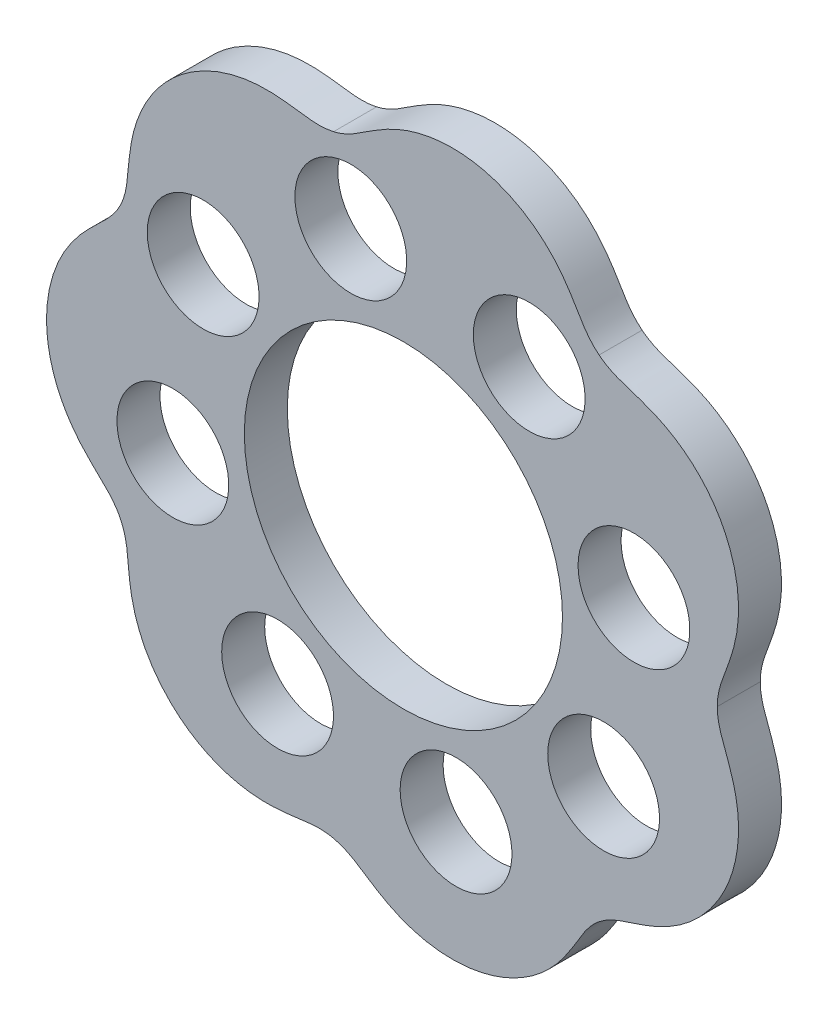
SolidWorks part; units mm, degrees
material "5052-H34"
ref_plane "Front Plane" through (0, 0, 0) normal (0, 0, 1) x (1, 0, 0)
ref_plane "Top Plane" through (0, 0, 0) normal (0, 1, 0) x (1, 0, 0)
ref_plane "Right Plane" through (0, 0, 0) normal (1, 0, 0) x (0, 0, -1)
sketch "Sketch1" plane through (0, 0, 0) normal (0, 0, 1) x (1, 0, 0)
  line L0 (0, 0) -> (37, 0) construction
  line L2 (37, 0) -> (39.5, 0) construction
  line L5 (24.6278, 30.8823) -> (0, 0) construction
  line L6 (0, 0) -> (-8.7896, 38.5096) construction
  line L7 (-35.5883, 17.1384) -> (0, 0) construction
  line L9 (-35.5883, -17.1384) -> (0, 0) construction
  line L10 (-8.7896, -38.5097) -> (0, 0) construction
  line L11 (24.6278, -30.8823) -> (0, 0) construction
  circle A0 centre (0, 0) radius 36 construction
  circle A1 centre (37, 0) radius 6 construction
  spline S0 degree 4 poles (39.9483, -2.12) (39.9195, -2.0383) (39.8632, -1.8746) (39.7822, -1.6278) (39.6848, -1.2955) (39.6113, -0.995) (39.5602, -0.7266) (39.5276, -0.4967) (39.5088, -0.2963) (39.4998, -0.0928) (39.4991, 0.0501) (39.505, 0.2155) (39.5157, 0.3724) (39.5329, 0.5353) (39.558, 0.7077) (39.6011, 0.9443) (39.6734, 1.255) (39.779, 1.6227) (39.9203, 2.0472) (40.0768, 2.4805) (40.3026, 3.083) (40.5945, 3.8559) (41.0315, 5.0877) (41.5249, 6.8077) (41.9013, 8.8642) (42.0339, 11.2502) (41.8633, 13.6337) (41.3936, 15.9767) (40.6339, 18.2422) (39.5972, 20.395) (38.2996, 22.4015) (36.7607, 24.2296) (35.0035, 25.849) (33.2989, 27.0601) (31.7392, 27.9386) (30.3866, 28.5643) (29.2788, 29.0047) (28.3249, 29.3341) (27.5386, 29.5876) (26.9268, 29.7867) (26.4905, 29.9345) (26.0706, 30.0887) (25.717, 30.2355) (25.4294, 30.3725) (25.184, 30.5045) (25.0052, 30.6109) (24.8304, 30.7289) (24.6664, 30.8504) (24.5552, 30.94) (24.4016, 31.074) (24.2567, 31.2136) (24.0973, 31.3824) (23.9194, 31.5897) (23.7303, 31.8345) (23.5312, 32.1179) (23.3886, 32.3351) (23.2958, 32.4812) (23.2499, 32.5546) knots 0 0 0 0 0 0.00783 0.015661 0.023491 0.031321 0.035802 0.040282 0.044763 0.049243 0.052611 0.055979 0.059347 0.062715 0.06731 0.071905 0.081096 0.091513 0.101931 0.112349 0.122766 0.149711 0.176657 0.230547 0.284438 0.338328 0.392219 0.446109 0.5 0.553891 0.607781 0.661672 0.715562 0.769453 0.796398 0.823343 0.850289 0.877234 0.887651 0.898069 0.908487 0.918904 0.928095 0.93269 0.937285 0.944021 0.947389 0.950757 0.955237 0.959718 0.964198 0.968679 0.976509 0.984339 0.99217 1 1 1 1 1 construction
  spline S1 degree 4 poles (39.5, 0) (39.5, 0.0336) (39.5009, 0.1009) (39.505, 0.2155) (39.5157, 0.3724) (39.5329, 0.5353) (39.558, 0.7077) (39.6011, 0.9443) (39.6734, 1.255) (39.779, 1.6227) (39.9203, 2.0472) (40.0768, 2.4805) (40.3026, 3.083) (40.5945, 3.8559) (41.0315, 5.0877) (41.5249, 6.8077) (41.9013, 8.8642) (42.0339, 11.2502) (41.8633, 13.6337) (41.3936, 15.9767) (40.6339, 18.2422) (39.5972, 20.395) (38.2996, 22.4015) (36.7607, 24.2296) (35.0035, 25.849) (33.2989, 27.0601) (31.7392, 27.9386) (30.3866, 28.5643) (29.2788, 29.0047) (28.3249, 29.3341) (27.5386, 29.5876) (26.9268, 29.7867) (26.4905, 29.9345) (26.0706, 30.0887) (25.717, 30.2355) (25.4294, 30.3725) (25.184, 30.5045) (25.0052, 30.6109) (24.8304, 30.7289) (24.7073, 30.8201) (24.6541, 30.8614) (24.6278, 30.8823) knots 0.049243 0.049243 0.049243 0.049243 0.049243 0.052611 0.055979 0.059347 0.062715 0.06731 0.071905 0.081096 0.091513 0.101931 0.112349 0.122766 0.149711 0.176657 0.230547 0.284438 0.338328 0.392219 0.446109 0.5 0.553891 0.607781 0.661672 0.715562 0.769453 0.796398 0.823343 0.850289 0.877234 0.887651 0.898069 0.908487 0.918904 0.928095 0.93269 0.937285 0.944021 0.947389 0.950757 0.950757 0.950757 0.950757 0.950757 construction
  spline S2 degree 4 poles (23.2499, -32.5546) (23.2958, -32.4812) (23.3886, -32.3351) (23.5312, -32.1179) (23.7303, -31.8345) (23.9194, -31.5897) (24.0973, -31.3824) (24.2568, -31.2136) (24.4016, -31.074) (24.5552, -30.9401) (24.6665, -30.8504) (24.7994, -30.7519) (24.9287, -30.6624) (25.0669, -30.5743) (25.2173, -30.4865) (25.4292, -30.3727) (25.7171, -30.2354) (26.0705, -30.0887) (26.4905, -29.9345) (26.9268, -29.7867) (27.5387, -29.5876) (28.3249, -29.334) (29.5605, -28.9076) (31.2128, -28.2209) (33.0554, -27.233) (35.0035, -25.8491) (36.7607, -24.2296) (38.2996, -22.4016) (39.5971, -20.395) (40.6339, -18.2422) (41.3936, -15.9767) (41.8634, -13.6337) (42.0339, -11.2502) (41.9179, -9.1625) (41.6323, -7.3953) (41.2783, -5.9477) (40.9318, -4.807) (40.5946, -3.8558) (40.3026, -3.083) (40.0768, -2.4805) (39.9203, -2.0472) (39.779, -1.6228) (39.6734, -1.2549) (39.6011, -0.9446) (39.5513, -0.6704) (39.523, -0.4642) (39.5063, -0.254) (39.4991, -0.05) (39.4998, 0.0928) (39.5088, 0.2963) (39.5276, 0.4967) (39.5602, 0.7266) (39.6113, 0.995) (39.6848, 1.2955) (39.7822, 1.6278) (39.8632, 1.8746) (39.9195, 2.0383) (39.9483, 2.12) knots 0 0 0 0 0 0.00783 0.015661 0.023491 0.031321 0.035802 0.040282 0.044763 0.049243 0.052611 0.055979 0.059347 0.062715 0.06731 0.071905 0.081096 0.091513 0.101931 0.112349 0.122766 0.149711 0.176657 0.230547 0.284438 0.338328 0.392219 0.446109 0.5 0.553891 0.607781 0.661672 0.715562 0.769453 0.796398 0.823343 0.850289 0.877234 0.887651 0.898069 0.908487 0.918904 0.928095 0.93269 0.937285 0.944021 0.947389 0.950757 0.955237 0.959718 0.964198 0.968679 0.976509 0.984339 0.99217 1 1 1 1 1 construction
  spline S3 degree 4 poles (24.6278, -30.8823) (24.6541, -30.8614) (24.7073, -30.8201) (24.7994, -30.7519) (24.9287, -30.6624) (25.0669, -30.5743) (25.2173, -30.4865) (25.4292, -30.3727) (25.7171, -30.2354) (26.0705, -30.0887) (26.4905, -29.9345) (26.9268, -29.7867) (27.5387, -29.5876) (28.3249, -29.334) (29.5605, -28.9076) (31.2128, -28.2209) (33.0554, -27.233) (35.0035, -25.8491) (36.7607, -24.2296) (38.2996, -22.4016) (39.5971, -20.395) (40.6339, -18.2422) (41.3936, -15.9767) (41.8634, -13.6337) (42.0339, -11.2502) (41.9179, -9.1625) (41.6323, -7.3953) (41.2783, -5.9477) (40.9318, -4.807) (40.5946, -3.8558) (40.3026, -3.083) (40.0768, -2.4805) (39.9203, -2.0472) (39.779, -1.6228) (39.6734, -1.2549) (39.6011, -0.9446) (39.5513, -0.6704) (39.523, -0.4642) (39.5063, -0.254) (39.5009, -0.1009) (39.5, -0.0336) (39.5, 0) knots 0.049243 0.049243 0.049243 0.049243 0.049243 0.052611 0.055979 0.059347 0.062715 0.06731 0.071905 0.081096 0.091513 0.101931 0.112349 0.122766 0.149711 0.176657 0.230547 0.284438 0.338328 0.392219 0.446109 0.5 0.553891 0.607781 0.661672 0.715562 0.769453 0.796398 0.823343 0.850289 0.877234 0.887651 0.898069 0.908487 0.918904 0.928095 0.93269 0.937285 0.944021 0.947389 0.950757 0.950757 0.950757 0.950757 0.950757 construction
  spline S4 degree 4 poles (-10.9562, -38.475) (-10.8702, -38.4651) (-10.698, -38.4466) (-10.4393, -38.4226) (-10.0937, -38.4016) (-9.7844, -38.3968) (-9.5114, -38.4066) (-9.2799, -38.426) (-9.0804, -38.4523) (-8.88, -38.4888) (-8.7405, -38.5199) (-8.5806, -38.5624) (-8.43, -38.6078) (-8.275, -38.6609) (-8.1126, -38.7237) (-7.8915, -38.8184) (-7.6046, -38.9579) (-7.2696, -39.1427) (-6.8872, -39.375) (-6.4996, -39.6239) (-5.9625, -39.9782) (-5.2739, -40.4348) (-4.1702, -41.1349) (-2.6031, -41.9986) (-0.6819, -42.8232) (1.6147, -43.4834) (3.9765, -43.8475) (6.3652, -43.911) (8.7429, -43.6744) (11.0725, -43.1427) (13.3174, -42.3241) (15.4421, -41.2306) (17.4119, -39.8778) (18.9719, -38.4855) (20.1754, -37.1604) (21.0865, -35.981) (21.7623, -34.9989) (22.2957, -34.1422) (22.7178, -33.432) (23.0481, -32.8798) (23.2893, -32.4874) (23.5331, -32.1123) (23.7549, -31.8003) (23.9524, -31.5503) (24.1357, -31.3404) (24.2793, -31.1898) (24.4332, -31.0457) (24.5882, -30.9128) (24.7002, -30.8243) (24.865, -30.7045) (25.0333, -30.5943) (25.2335, -30.4763) (25.4752, -30.3491) (25.7559, -30.2191) (26.0764, -30.0881) (26.3199, -29.9975) (26.4831, -29.9395) (26.5648, -29.9111) knots 0 0 0 0 0 0.00783 0.015661 0.023491 0.031321 0.035802 0.040282 0.044763 0.049243 0.052611 0.055979 0.059347 0.062715 0.06731 0.071905 0.081096 0.091513 0.101931 0.112349 0.122766 0.149711 0.176657 0.230547 0.284438 0.338328 0.392219 0.446109 0.5 0.553891 0.607781 0.661672 0.715562 0.769453 0.796398 0.823343 0.850289 0.877234 0.887651 0.898069 0.908487 0.918904 0.928095 0.93269 0.937285 0.944021 0.947389 0.950757 0.955237 0.959718 0.964198 0.968679 0.976509 0.984339 0.99217 1 1 1 1 1 construction
  spline S5 degree 4 poles (-8.7896, -38.5097) (-8.7568, -38.5171) (-8.6914, -38.533) (-8.5806, -38.5624) (-8.43, -38.6078) (-8.275, -38.6609) (-8.1126, -38.7237) (-7.8915, -38.8184) (-7.6046, -38.9579) (-7.2696, -39.1427) (-6.8872, -39.375) (-6.4996, -39.6239) (-5.9625, -39.9782) (-5.2739, -40.4348) (-4.1702, -41.1349) (-2.6031, -41.9986) (-0.6819, -42.8232) (1.6147, -43.4834) (3.9765, -43.8475) (6.3652, -43.911) (8.7429, -43.6744) (11.0725, -43.1427) (13.3174, -42.3241) (15.4421, -41.2306) (17.4119, -39.8778) (18.9719, -38.4855) (20.1754, -37.1604) (21.0865, -35.981) (21.7623, -34.9989) (22.2957, -34.1422) (22.7178, -33.432) (23.0481, -32.8798) (23.2893, -32.4874) (23.5331, -32.1123) (23.7549, -31.8003) (23.9524, -31.5503) (24.1357, -31.3404) (24.2793, -31.1898) (24.4332, -31.0457) (24.5495, -30.946) (24.6016, -30.9033) (24.6278, -30.8823) knots 0.049243 0.049243 0.049243 0.049243 0.049243 0.052611 0.055979 0.059347 0.062715 0.06731 0.071905 0.081096 0.091513 0.101931 0.112349 0.122766 0.149711 0.176657 0.230547 0.284438 0.338328 0.392219 0.446109 0.5 0.553891 0.607781 0.661672 0.715562 0.769453 0.796398 0.823343 0.850289 0.877234 0.887651 0.898069 0.908487 0.918904 0.928095 0.93269 0.937285 0.944021 0.947389 0.950757 0.950757 0.950757 0.950757 0.950757 construction
  spline S6 degree 4 poles (-36.912, -15.4229) (-36.8506, -15.484) (-36.7288, -15.607) (-36.5488, -15.7943) (-36.3169, -16.0514) (-36.1203, -16.2903) (-35.9578, -16.5098) (-35.8286, -16.7029) (-35.7247, -16.8752) (-35.6284, -17.0547) (-35.5657, -17.1832) (-35.4992, -17.3347) (-35.4408, -17.4807) (-35.3857, -17.635) (-35.3335, -17.8012) (-35.2697, -18.0331) (-35.1999, -18.3443) (-35.1356, -18.7215) (-35.0787, -19.1653) (-35.0317, -19.6235) (-34.9737, -20.2643) (-34.9014, -21.0873) (-34.7606, -22.3868) (-34.4588, -24.1505) (-33.9057, -26.1667) (-32.99, -28.3739) (-31.8021, -30.4474) (-30.3624, -32.3545) (-28.6949, -34.066) (-26.8267, -35.5559) (-24.7871, -36.8007) (-22.6074, -37.78) (-20.3215, -38.4766) (-18.2604, -38.8281) (-16.474, -38.9429) (-14.9838, -38.9199) (-13.7946, -38.8359) (-12.7923, -38.7188) (-11.9739, -38.606) (-11.3362, -38.52) (-10.879, -38.4639) (-10.4338, -38.4206) (-10.0516, -38.3994) (-9.733, -38.3981) (-9.4546, -38.4105) (-9.2473, -38.4288) (-9.0386, -38.4593) (-8.8382, -38.4976) (-8.6991, -38.5301) (-8.5026, -38.5841) (-8.3115, -38.6471) (-8.0946, -38.73) (-7.8443, -38.8396) (-7.5677, -38.9781) (-7.2654, -39.147) (-7.0428, -39.2809) (-6.8957, -39.3722) (-6.8225, -39.4185) knots 0 0 0 0 0 0.00783 0.015661 0.023491 0.031321 0.035802 0.040282 0.044763 0.049243 0.052611 0.055979 0.059347 0.062715 0.06731 0.071905 0.081096 0.091513 0.101931 0.112349 0.122766 0.149711 0.176657 0.230547 0.284438 0.338328 0.392219 0.446109 0.5 0.553891 0.607781 0.661672 0.715562 0.769453 0.796398 0.823343 0.850289 0.877234 0.887651 0.898069 0.908487 0.918904 0.928095 0.93269 0.937285 0.944021 0.947389 0.950757 0.955237 0.959718 0.964198 0.968679 0.976509 0.984339 0.99217 1 1 1 1 1 construction
  spline S7 degree 4 poles (-35.5883, -17.1384) (-35.5737, -17.1687) (-35.5453, -17.2297) (-35.4992, -17.3347) (-35.4408, -17.4807) (-35.3857, -17.635) (-35.3335, -17.8012) (-35.2697, -18.0331) (-35.1999, -18.3443) (-35.1356, -18.7215) (-35.0787, -19.1653) (-35.0317, -19.6235) (-34.9737, -20.2643) (-34.9014, -21.0873) (-34.7606, -22.3868) (-34.4588, -24.1505) (-33.9057, -26.1667) (-32.99, -28.3739) (-31.8021, -30.4474) (-30.3624, -32.3545) (-28.6949, -34.066) (-26.8267, -35.5559) (-24.7871, -36.8007) (-22.6074, -37.78) (-20.3215, -38.4766) (-18.2604, -38.8281) (-16.474, -38.9429) (-14.9838, -38.9199) (-13.7946, -38.8359) (-12.7923, -38.7188) (-11.9739, -38.606) (-11.3362, -38.52) (-10.879, -38.4639) (-10.4338, -38.4206) (-10.0516, -38.3994) (-9.733, -38.3981) (-9.4546, -38.4105) (-9.2473, -38.4288) (-9.0386, -38.4593) (-8.8882, -38.4881) (-8.8223, -38.5022) (-8.7896, -38.5097) knots 0.049243 0.049243 0.049243 0.049243 0.049243 0.052611 0.055979 0.059347 0.062715 0.06731 0.071905 0.081096 0.091513 0.101931 0.112349 0.122766 0.149711 0.176657 0.230547 0.284438 0.338328 0.392219 0.446109 0.5 0.553891 0.607781 0.661672 0.715562 0.769453 0.796398 0.823343 0.850289 0.877234 0.887651 0.898069 0.908487 0.918904 0.928095 0.93269 0.937285 0.944021 0.947389 0.950757 0.950757 0.950757 0.950757 0.950757 construction
  spline S8 degree 4 poles (-35.0725, 19.243) (-35.0819, 19.1569) (-35.1022, 18.985) (-35.1364, 18.7274) (-35.1928, 18.3858) (-35.257, 18.0831) (-35.3273, 17.8192) (-35.3977, 17.5978) (-35.4677, 17.4092) (-35.5479, 17.2219) (-35.6093, 17.0929) (-35.6863, 16.9464) (-35.764, 16.8097) (-35.8503, 16.6704) (-35.9477, 16.526) (-36.0892, 16.3315) (-36.2891, 16.0829) (-36.5438, 15.7974) (-36.8553, 15.4763) (-37.1842, 15.1538) (-37.6491, 14.7089) (-38.2475, 14.1393) (-39.1757, 13.219) (-40.3664, 11.8834) (-41.5979, 10.1939) (-42.7526, 8.1018) (-43.6331, 5.8802) (-44.2264, 3.5655) (-44.5249, 1.1947) (-44.5249, -1.1948) (-44.2264, -3.5655) (-43.6331, -5.8803) (-42.7525, -8.1018) (-41.7422, -9.9324) (-40.7182, -11.4006) (-39.771, -12.5513) (-38.9639, -13.4287) (-38.2475, -14.1394) (-37.649, -14.7089) (-37.1842, -15.1538) (-36.8552, -15.4763) (-36.5438, -15.7974) (-36.2889, -16.083) (-36.0892, -16.3313) (-35.9254, -16.5567) (-35.8105, -16.7302) (-35.7042, -16.9123) (-35.6092, -17.0929) (-35.5478, -17.2219) (-35.4676, -17.4092) (-35.3976, -17.5978) (-35.3272, -17.8192) (-35.2569, -18.0831) (-35.1927, -18.3858) (-35.1363, -18.7274) (-35.1021, -18.985) (-35.0818, -19.1569) (-35.0724, -19.243) knots 0 0 0 0 0 0.00783 0.015661 0.023491 0.031321 0.035802 0.040282 0.044763 0.049243 0.052611 0.055979 0.059347 0.062715 0.06731 0.071905 0.081096 0.091513 0.101931 0.112349 0.122766 0.149711 0.176657 0.230547 0.284438 0.338328 0.392219 0.446109 0.5 0.553891 0.607781 0.661672 0.715562 0.769453 0.796398 0.823343 0.850289 0.877234 0.887651 0.898069 0.908487 0.918904 0.928095 0.93269 0.937285 0.944021 0.947389 0.950757 0.955237 0.959718 0.964198 0.968679 0.976509 0.984339 0.99217 1 1 1 1 1 construction
  spline S9 degree 4 poles (-35.5883, 17.1384) (-35.6029, 17.1082) (-35.6329, 17.0479) (-35.6863, 16.9464) (-35.764, 16.8097) (-35.8503, 16.6704) (-35.9477, 16.526) (-36.0892, 16.3315) (-36.2891, 16.0829) (-36.5438, 15.7974) (-36.8553, 15.4763) (-37.1842, 15.1538) (-37.6491, 14.7089) (-38.2475, 14.1393) (-39.1757, 13.219) (-40.3664, 11.8834) (-41.5979, 10.1939) (-42.7526, 8.1018) (-43.6331, 5.8802) (-44.2264, 3.5655) (-44.5249, 1.1947) (-44.5249, -1.1948) (-44.2264, -3.5655) (-43.6331, -5.8803) (-42.7525, -8.1018) (-41.7422, -9.9324) (-40.7182, -11.4006) (-39.771, -12.5513) (-38.9639, -13.4287) (-38.2475, -14.1394) (-37.649, -14.7089) (-37.1842, -15.1538) (-36.8552, -15.4763) (-36.5438, -15.7974) (-36.2889, -16.083) (-36.0892, -16.3313) (-35.9254, -16.5567) (-35.8105, -16.7302) (-35.7042, -16.9123) (-35.6329, -17.0479) (-35.6028, -17.1082) (-35.5883, -17.1384) knots 0.049243 0.049243 0.049243 0.049243 0.049243 0.052611 0.055979 0.059347 0.062715 0.06731 0.071905 0.081096 0.091513 0.101931 0.112349 0.122766 0.149711 0.176657 0.230547 0.284438 0.338328 0.392219 0.446109 0.5 0.553891 0.607781 0.661672 0.715562 0.769453 0.796398 0.823343 0.850289 0.877234 0.887651 0.898069 0.908487 0.918904 0.928095 0.93269 0.937285 0.944021 0.947389 0.950757 0.950757 0.950757 0.950757 0.950757 construction
  spline S10 degree 4 poles (-6.8225, 39.4184) (-6.8957, 39.3722) (-7.0428, 39.2808) (-7.2654, 39.1469) (-7.5677, 38.978) (-7.8444, 38.8395) (-8.0946, 38.7299) (-8.3115, 38.647) (-8.5027, 38.5841) (-8.6991, 38.53) (-8.8382, 38.4976) (-9.0008, 38.4665) (-9.1561, 38.442) (-9.3188, 38.4226) (-9.4924, 38.4087) (-9.7327, 38.3981) (-10.0517, 38.3993) (-10.4337, 38.4205) (-10.879, 38.4638) (-11.3362, 38.5199) (-11.9739, 38.606) (-12.7923, 38.7187) (-14.0905, 38.8706) (-15.8772, 38.9688) (-17.9659, 38.8782) (-20.3216, 38.4766) (-22.6074, 37.7799) (-24.7871, 36.8006) (-26.8267, 35.5558) (-28.6949, 34.066) (-30.3624, 32.3545) (-31.8022, 30.4474) (-32.99, 28.3739) (-33.7914, 26.4426) (-34.3008, 24.7266) (-34.6099, 23.2686) (-34.7927, 22.0906) (-34.9016, 21.0873) (-34.9737, 20.2643) (-35.0318, 19.6235) (-35.0788, 19.1652) (-35.1356, 18.7215) (-35.2001, 18.3442) (-35.2696, 18.0333) (-35.3437, 17.7647) (-35.4077, 17.5667) (-35.4838, 17.37) (-35.5658, 17.1831) (-35.6284, 17.0547) (-35.7248, 16.8752) (-35.8287, 16.7029) (-35.9578, 16.5098) (-36.1204, 16.2903) (-36.3169, 16.0514) (-36.5489, 15.7943) (-36.7289, 15.607) (-36.8507, 15.484) (-36.9121, 15.4229) knots 0 0 0 0 0 0.00783 0.015661 0.023491 0.031321 0.035802 0.040282 0.044763 0.049243 0.052611 0.055979 0.059347 0.062715 0.06731 0.071905 0.081096 0.091513 0.101931 0.112349 0.122766 0.149711 0.176657 0.230547 0.284438 0.338328 0.392219 0.446109 0.5 0.553891 0.607781 0.661672 0.715562 0.769453 0.796398 0.823343 0.850289 0.877234 0.887651 0.898069 0.908487 0.918904 0.928095 0.93269 0.937285 0.944021 0.947389 0.950757 0.955237 0.959718 0.964198 0.968679 0.976509 0.984339 0.99217 1 1 1 1 1 construction
  spline S11 degree 4 poles (-8.7896, 38.5096) (-8.8223, 38.5021) (-8.8882, 38.488) (-9.0008, 38.4665) (-9.1561, 38.442) (-9.3188, 38.4226) (-9.4924, 38.4087) (-9.7327, 38.3981) (-10.0517, 38.3993) (-10.4337, 38.4205) (-10.879, 38.4638) (-11.3362, 38.5199) (-11.9739, 38.606) (-12.7923, 38.7187) (-14.0905, 38.8706) (-15.8772, 38.9688) (-17.9659, 38.8782) (-20.3216, 38.4766) (-22.6074, 37.7799) (-24.7871, 36.8006) (-26.8267, 35.5558) (-28.6949, 34.066) (-30.3624, 32.3545) (-31.8022, 30.4474) (-32.99, 28.3739) (-33.7914, 26.4426) (-34.3008, 24.7266) (-34.6099, 23.2686) (-34.7927, 22.0906) (-34.9016, 21.0873) (-34.9737, 20.2643) (-35.0318, 19.6235) (-35.0788, 19.1652) (-35.1356, 18.7215) (-35.2001, 18.3442) (-35.2696, 18.0333) (-35.3437, 17.7647) (-35.4077, 17.5667) (-35.4838, 17.37) (-35.5454, 17.2297) (-35.5738, 17.1687) (-35.5883, 17.1384) knots 0.049243 0.049243 0.049243 0.049243 0.049243 0.052611 0.055979 0.059347 0.062715 0.06731 0.071905 0.081096 0.091513 0.101931 0.112349 0.122766 0.149711 0.176657 0.230547 0.284438 0.338328 0.392219 0.446109 0.5 0.553891 0.607781 0.661672 0.715562 0.769453 0.796398 0.823343 0.850289 0.877234 0.887651 0.898069 0.908487 0.918904 0.928095 0.93269 0.937285 0.944021 0.947389 0.950757 0.950757 0.950757 0.950757 0.950757 construction
  spline S12 degree 4 poles (26.5648, 29.9111) (26.4831, 29.9395) (26.3199, 29.9975) (26.0764, 30.0881) (25.7559, 30.2191) (25.4752, 30.3491) (25.2335, 30.4763) (25.0333, 30.5943) (24.865, 30.7045) (24.7003, 30.8243) (24.5881, 30.9129) (24.4624, 31.0206) (24.3465, 31.1268) (24.2299, 31.2418) (24.1107, 31.3689) (23.9526, 31.5502) (23.7547, 31.8004) (23.5331, 32.1122) (23.2893, 32.4874) (23.0481, 32.8798) (22.7179, 33.4321) (22.2956, 34.1422) (21.605, 35.2519) (20.5678, 36.71) (19.1947, 38.2865) (17.412, 39.8778) (15.4421, 41.2306) (13.3174, 42.3241) (11.0725, 43.1427) (8.7429, 43.6744) (6.3651, 43.9109) (3.9764, 43.8475) (1.6147, 43.4834) (-0.3949, 42.9058) (-2.0542, 42.2341) (-3.3868, 41.5668) (-4.4218, 40.9751) (-5.274, 40.4348) (-5.9624, 39.9781) (-6.4996, 39.6239) (-6.8872, 39.3749) (-7.2696, 39.1427) (-7.6048, 38.9578) (-7.8912, 38.8184) (-8.1475, 38.7088) (-8.3421, 38.6354) (-8.5433, 38.5723) (-8.7406, 38.5198) (-8.88, 38.4887) (-9.0804, 38.4522) (-9.2799, 38.426) (-9.5114, 38.4066) (-9.7844, 38.3967) (-10.0937, 38.4015) (-10.4393, 38.4225) (-10.698, 38.4465) (-10.8702, 38.465) (-10.9562, 38.4749) knots 0 0 0 0 0 0.00783 0.015661 0.023491 0.031321 0.035802 0.040282 0.044763 0.049243 0.052611 0.055979 0.059347 0.062715 0.06731 0.071905 0.081096 0.091513 0.101931 0.112349 0.122766 0.149711 0.176657 0.230547 0.284438 0.338328 0.392219 0.446109 0.5 0.553891 0.607781 0.661672 0.715562 0.769453 0.796398 0.823343 0.850289 0.877234 0.887651 0.898069 0.908487 0.918904 0.928095 0.93269 0.937285 0.944021 0.947389 0.950757 0.955237 0.959718 0.964198 0.968679 0.976509 0.984339 0.99217 1 1 1 1 1 construction
  spline S13 degree 4 poles (24.6278, 30.8823) (24.6016, 30.9033) (24.5495, 30.946) (24.4624, 31.0206) (24.3465, 31.1268) (24.2299, 31.2418) (24.1107, 31.3689) (23.9526, 31.5502) (23.7547, 31.8004) (23.5331, 32.1122) (23.2893, 32.4874) (23.0481, 32.8798) (22.7179, 33.4321) (22.2956, 34.1422) (21.605, 35.2519) (20.5678, 36.71) (19.1947, 38.2865) (17.412, 39.8778) (15.4421, 41.2306) (13.3174, 42.3241) (11.0725, 43.1427) (8.7429, 43.6744) (6.3651, 43.9109) (3.9764, 43.8475) (1.6147, 43.4834) (-0.3949, 42.9058) (-2.0542, 42.2341) (-3.3868, 41.5668) (-4.4218, 40.9751) (-5.274, 40.4348) (-5.9624, 39.9781) (-6.4996, 39.6239) (-6.8872, 39.3749) (-7.2696, 39.1427) (-7.6048, 38.9578) (-7.8912, 38.8184) (-8.1475, 38.7088) (-8.3421, 38.6354) (-8.5433, 38.5723) (-8.6914, 38.5329) (-8.7569, 38.5171) (-8.7896, 38.5096) knots 0.049243 0.049243 0.049243 0.049243 0.049243 0.052611 0.055979 0.059347 0.062715 0.06731 0.071905 0.081096 0.091513 0.101931 0.112349 0.122766 0.149711 0.176657 0.230547 0.284438 0.338328 0.392219 0.446109 0.5 0.553891 0.607781 0.661672 0.715562 0.769453 0.796398 0.823343 0.850289 0.877234 0.887651 0.898069 0.908487 0.918904 0.928095 0.93269 0.937285 0.944021 0.947389 0.950757 0.950757 0.950757 0.950757 0.950757 construction
  spline S14 degree 1 poles (22.7574, -28.5368) (36.5, 0) knots 0 0 1 1 construction
  spline S15 degree 1 poles (36.5, 0) (22.7574, 28.5368) knots 0 0 1 1 construction
  spline S16 degree 1 poles (22.7574, 28.5368) (-8.122, 35.5848) knots 0 0 1 1 construction
  spline S17 degree 1 poles (-8.122, 35.5848) (-32.8854, 15.8368) knots 0 0 1 1 construction
  spline S18 degree 1 poles (-32.8854, 15.8368) (-32.8854, -15.8368) knots 0 0 1 1 construction
  spline S19 degree 1 poles (-32.8854, -15.8368) (-8.122, -35.5849) knots 0 0 1 1 construction
  spline S20 degree 1 poles (-8.122, -35.5849) (22.7574, -28.5368) knots 0 0 1 1 construction
  spline S21 degree 3 poles (22.7574, -28.5368) (22.8939, -28.428) (23.1702, -28.2236) (23.7922, -27.8312) (24.4834, -27.4927) (25.2467, -27.1904) (26.1429, -26.883) (27.1232, -26.5727) (28.1933, -26.2047) (29.2024, -25.8042) (30.4901, -25.2061) (32.0033, -24.3212) (33.6599, -23.033) (35.6234, -21.0378) (37.5563, -18.0861) (38.6589, -14.7346) (38.9945, -11.9555) (38.9689, -9.8573) (38.7171, -8.1222) (38.3821, -6.7429) (38.0658, -5.7039) (37.6865, -4.6382) (37.3178, -3.6779) (36.9994, -2.7859) (36.7599, -1.9999) (36.5939, -1.2519) (36.5125, -0.5178) (36.5, -0.1747) (36.5, 0) knots 0.049243 0.049243 0.049243 0.049243 0.056286 0.063329 0.077415 0.091501 0.105587 0.13376 0.161932 0.190104 0.218277 0.274621 0.330966 0.387311 0.5 0.612689 0.669034 0.725379 0.781723 0.809896 0.838068 0.86624 0.894413 0.908499 0.922585 0.936671 0.943714 0.950757 0.950757 0.950757 0.950757
  spline S22 degree 3 poles (36.5, 0) (36.5, 0.1747) (36.5125, 0.5181) (36.5935, 1.249) (36.7599, 2.0005) (36.9994, 2.7857) (37.3178, 3.6781) (37.6864, 4.6379) (38.0659, 5.7041) (38.382, 6.7427) (38.7172, 8.1224) (38.9688, 9.8572) (38.9946, 11.9555) (38.6588, 14.7346) (37.5563, 18.0861) (35.6234, 21.0378) (33.6599, 23.033) (32.0034, 24.3212) (30.4899, 25.2061) (29.2026, 25.8042) (28.1931, 26.2047) (27.1235, 26.5726) (26.1428, 26.8831) (25.2469, 27.1903) (24.483, 27.4931) (23.7946, 27.8297) (23.17, 28.2238) (22.894, 28.4279) (22.7574, 28.5368) knots 0.049243 0.049243 0.049243 0.049243 0.056286 0.063329 0.077415 0.091501 0.105587 0.13376 0.161932 0.190104 0.218277 0.274621 0.330966 0.387311 0.5 0.612689 0.669034 0.725379 0.781723 0.809896 0.838068 0.86624 0.894413 0.908499 0.922585 0.936671 0.943714 0.950757 0.950757 0.950757 0.950757
  spline S23 degree 3 poles (22.7574, 28.5368) (22.6208, 28.6457) (22.3601, 28.8696) (21.8391, 29.3887) (21.3554, 29.9873) (20.8908, 30.6642) (20.3916, 31.4695) (19.871, 32.3561) (19.2741, 33.3175) (18.6591, 34.2122) (17.7894, 35.3346) (16.59, 36.6129) (14.9655, 37.9413) (12.5834, 39.4116) (9.2756, 40.6392) (5.7627, 40.9683) (2.9787, 40.6772) (0.9387, 40.1853) (-0.6969, 39.5536) (-1.967, 38.9201) (-2.9096, 38.3805) (-3.8642, 37.7737) (-4.7183, 37.2005) (-5.5171, 36.6916) (-6.2301, 36.2832) (-6.9224, 35.9549) (-7.62, 35.7122) (-7.9517, 35.6237) (-8.122, 35.5848) knots 0.049243 0.049243 0.049243 0.049243 0.056286 0.063329 0.077415 0.091501 0.105587 0.13376 0.161932 0.190104 0.218277 0.274621 0.330966 0.387311 0.5 0.612689 0.669034 0.725379 0.781723 0.809896 0.838068 0.86624 0.894413 0.908499 0.922585 0.936671 0.943714 0.950757 0.950757 0.950757 0.950757
  spline S24 degree 3 poles (-8.122, 35.5848) (-8.2923, 35.5459) (-8.6299, 35.4817) (-9.3605, 35.398) (-10.1302, 35.393) (-10.949, 35.4518) (-11.8899, 35.5636) (-12.9077, 35.7094) (-14.0315, 35.8422) (-15.1145, 35.9192) (-16.5342, 35.939) (-18.2815, 35.7983) (-20.3329, 35.3565) (-22.9676, 34.4108) (-25.9898, 32.5901) (-28.4374, 30.0489) (-29.9456, 27.6907) (-30.8329, 25.7891) (-31.3589, 24.1165) (-31.6555, 22.7285) (-31.8213, 21.6551) (-31.942, 20.5304) (-32.0264, 19.5053) (-32.1266, 18.5635) (-32.2518, 17.7514) (-32.4268, 17.0054) (-32.672, 16.3087) (-32.8096, 15.9942) (-32.8854, 15.8368) knots 0.049243 0.049243 0.049243 0.049243 0.056286 0.063329 0.077415 0.091501 0.105587 0.13376 0.161932 0.190104 0.218277 0.274621 0.330966 0.387311 0.5 0.612689 0.669034 0.725378 0.781723 0.809895 0.838068 0.86624 0.894412 0.908499 0.922585 0.936671 0.943714 0.950757 0.950757 0.950757 0.950757
  spline S25 degree 3 poles (-32.8854, 15.8368) (-32.9612, 15.6794) (-33.1215, 15.3754) (-33.5116, 14.752) (-33.9875, 14.1471) (-34.544, 13.5436) (-35.2181, 12.8777) (-35.9667, 12.1729) (-36.7711, 11.377) (-37.5066, 10.5783) (-38.4072, 9.4807) (-39.3866, 8.0269) (-40.3203, 6.1475) (-41.2236, 3.498) (-41.6843, 0) (-41.2236, -3.498) (-40.3202, -6.1475) (-39.3867, -8.0269) (-38.407, -9.4809) (-37.5067, -10.5782) (-36.7709, -11.3771) (-35.9668, -12.1727) (-35.2179, -12.8779) (-34.5441, -13.5434) (-33.9872, -14.1476) (-33.5131, -14.7496) (-33.1213, -15.3757) (-32.9612, -15.6793) (-32.8854, -15.8368) knots 0.049243 0.049243 0.049243 0.049243 0.056286 0.063329 0.077415 0.091501 0.105588 0.13376 0.161932 0.190105 0.218277 0.274621 0.330966 0.387311 0.5 0.612689 0.669034 0.725379 0.781723 0.809896 0.838068 0.86624 0.894413 0.908499 0.922585 0.936671 0.943714 0.950757 0.950757 0.950757 0.950757
  spline S26 degree 3 poles (-32.8854, -15.8368) (-32.8096, -15.9941) (-32.6718, -16.309) (-32.4277, -17.0027) (-32.2515, -17.7519) (-32.1266, -18.5633) (-32.0263, -19.5054) (-31.942, -20.5302) (-31.8213, -21.6553) (-31.6554, -22.7283) (-31.3588, -24.1168) (-30.8328, -25.789) (-29.9456, -27.6907) (-28.4373, -30.0489) (-25.9897, -32.5901) (-22.9676, -34.4109) (-20.3329, -35.3565) (-18.2815, -35.7984) (-16.5339, -35.939) (-15.1147, -35.9193) (-14.0313, -35.8421) (-12.908, -35.7096) (-11.8897, -35.5637) (-10.9492, -35.4518) (-10.1296, -35.3932) (-9.3634, -35.3978) (-8.6296, -35.4818) (-8.2923, -35.546) (-8.122, -35.5849) knots 0.049243 0.049243 0.049243 0.049243 0.056286 0.063329 0.077415 0.091501 0.105587 0.13376 0.161932 0.190104 0.218277 0.274621 0.330966 0.387311 0.5 0.612689 0.669034 0.725379 0.781723 0.809896 0.838068 0.86624 0.894413 0.908499 0.922585 0.936671 0.943714 0.950757 0.950757 0.950757 0.950757
  spline S27 degree 3 poles (-8.122, -35.5849) (-7.9517, -35.6237) (-7.6197, -35.7124) (-6.9251, -35.954) (-6.2295, -36.2834) (-5.5172, -36.6916) (-4.7181, -37.2006) (-3.8644, -37.7736) (-2.9094, -38.3808) (-1.9671, -38.92) (-0.6966, -39.5539) (0.9387, -40.1852) (2.9787, -40.6773) (5.7628, -40.9683) (9.2756, -40.6392) (12.5834, -39.4116) (14.9655, -37.9413) (16.59, -36.613) (17.7895, -35.3343) (18.659, -34.2124) (19.2741, -33.3173) (19.8709, -32.3564) (20.3917, -31.4694) (20.8906, -30.6643) (21.3558, -29.9869) (21.8372, -29.3907) (22.3603, -28.8694) (22.6208, -28.6458) (22.7574, -28.5368) knots 0.049243 0.049243 0.049243 0.049243 0.056286 0.063329 0.077415 0.091501 0.105587 0.13376 0.161932 0.190104 0.218277 0.274621 0.330966 0.387311 0.5 0.612689 0.669034 0.725379 0.781723 0.809896 0.838068 0.86624 0.894413 0.908499 0.922585 0.936671 0.943714 0.950757 0.950757 0.950757 0.950757
  point P24 (0, 0)
  point P28 (0, 0)
  point P29 (0, 0)
  point P30 (0, 0)
  point P32 (0, 0)
  point P33 (0, 0)
  point P35 (0, 0)
  point P43 (0, 0)
  point P46 (0, 0)
  point P54 (0, 0)
  dimension "a" = 72
  dimension "b" = 12
  dimension "c" = 2.5
  dimension "D1" = 3
extrude "Boss-Extrude1" add sketch "Sketch1" against normal blind 5
sketch "ｽｹｯﾁ2" plane through (0, 0, -5) normal (0, 0, -1) x (-1, 0, 0)
  line L0 (0, 0) -> (8.7896, 38.5096) construction
  line L1 (0, 0) -> (6.1193, 26.8105) construction
  circle A0 centre (0, 0) radius 27.5 construction
  circle A1 centre (6.1193, 26.8105) radius 6.5
  circle A2 centre (23.2849, 14.6309) radius 6.5
  circle A3 centre (26.8105, -6.1193) radius 6.5
  circle A4 centre (14.6309, -23.2849) radius 6.5
  circle A5 centre (-6.1193, -26.8105) radius 6.5
  circle A6 centre (-23.2849, -14.6309) radius 6.5
  circle A7 centre (-26.8105, 6.1193) radius 6.5
  circle A8 centre (-14.6309, 23.2849) radius 6.5
  circle A10 centre (0, 0) radius 18.5
  point P23 (0, 0)
  dimension "D1" = 55
  dimension "D2" = 13
  dimension "D4" = 37
  dimension "D5" = 0
  dimension "D3" = 8
extrude "ｶｯﾄ - 押し出し1" cut sketch "ｽｹｯﾁ2" against normal through all
equation "\"a\"= 72"
equation "\"b\"= 12"
equation "\"r\"= 3"
equation "\"m\"= 7"
equation "\"a@Sketch1\"= \"a\""
equation "\"b@Sketch1\"= \"b\""
equation "\"c\"= 2.5"
equation "\"c@Sketch1\"= \"c\""
